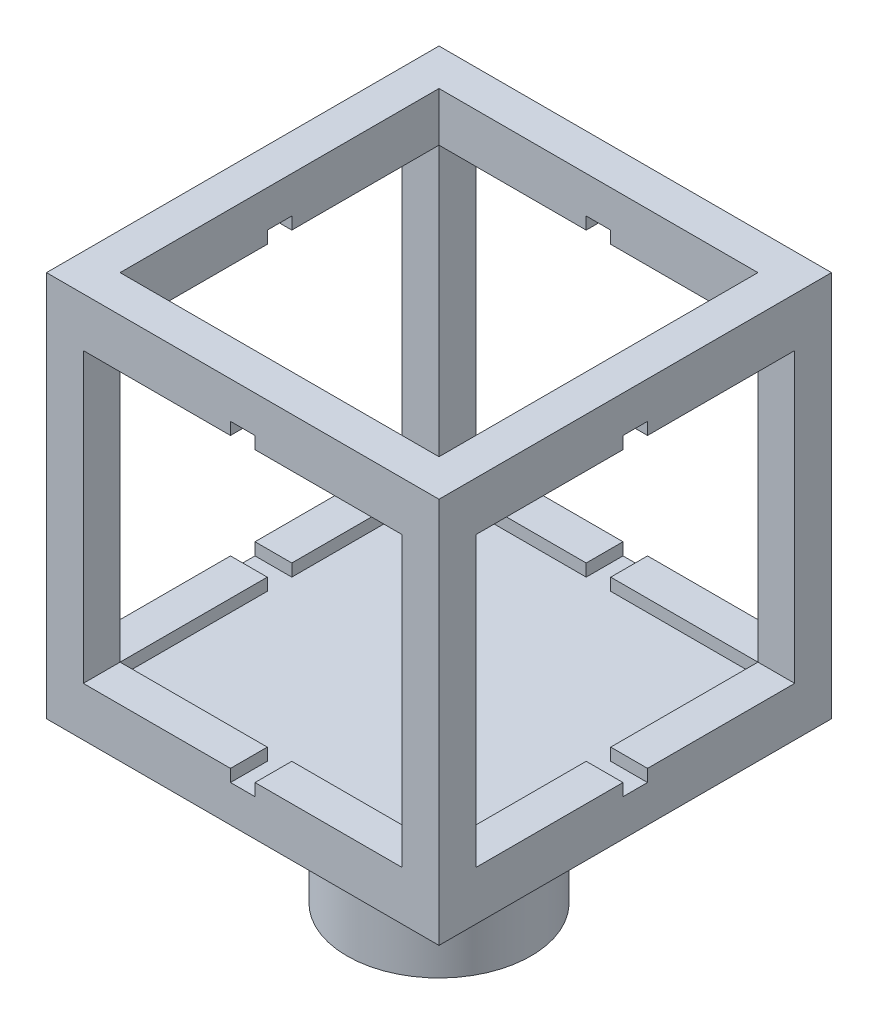
SolidWorks part; units mm, degrees
ref_plane "Plan de face" through (0, 0, 0) normal (0, 0, 1) x (1, 0, 0)
ref_plane "Plan de dessus" through (0, 0, 0) normal (0, 1, 0) x (1, 0, 0)
ref_plane "Plan de droite" through (0, 0, 0) normal (1, 0, 0) x (0, 0, -1)
sketch "Esquisse1" plane through (0, 0, 0) normal (0, 1, 0) x (1, 0, 0)
  circle A0 centre (0, 0) radius 7.5
  dimension "D1" = 15
extrude "Boss.-Extru.1" add sketch "Esquisse1" against normal blind 12
sketch "Esquisse2" plane through (0, 0, 0) normal (0, 1, 0) x (1, 0, 0)
  circle A0 centre (0, 0) radius 8.5
  dimension "D1" = 17
extrude "Boss.-Extru.2" add sketch "Esquisse2" along normal blind 1
sketch "Esquisse3" plane through (0, 1, 0) normal (0, 1, 0) x (1, 0, 0)
  line L1 (-13, -13) -> (13, -13)
  line L2 (-13, -13) -> (-13, 13)
  line L3 (-13, 13) -> (13, 13)
  line L4 (13, -13) -> (13, 13)
  line L5 (-13, -13) -> (13, 13) construction
  line L6 (-13, 13) -> (13, -13) construction
  line L7 (-16, -16) -> (16, -16)
  line L8 (-16, -16) -> (-16, 16)
  line L9 (-16, 16) -> (16, 16)
  line L10 (16, -16) -> (16, 16)
  line L11 (-16, -16) -> (16, 16) construction
  line L12 (-16, 16) -> (16, -16) construction
  point P0 (0, 0)
  point P6 (0, 0)
  circle M7 centre (0, 0) radius 8.5
  dimension "D1" = 26
  dimension "D2" = 26
  dimension "D3" = 3
  dimension "D4" = 3
extrude "Boss.-Extru.3" add sketch "Esquisse3" along normal blind 31.5 separate body contours L1 L4 L3 L2 M7 | M7 | L7 L10 L9 L8 L4 L1 L2 L3
sketch3d "Esquisse3D1" plane through (0, 0, 0) normal (0, 0, 1) x (1, 0, 0)
  dimension "D1" = 3
sketch "Esquisse7" plane through (0, 4, 0) normal (0, -1, 0) x (-1, 0, 0)
  line L1 (-13, 13) -> (13, 13)
  line L2 (-13, 13) -> (-13, -13)
  line L3 (-13, -13) -> (13, -13)
  line L4 (13, 13) -> (13, -13)
extrude "Enlèv. mat.-Extru.2" cut sketch "Esquisse7" against normal through all
sketch "Esquisse8" plane through (-16, 0, 0) normal (-1, 0, 0) x (0, 0, 1)
  line L0 (-16, 32.5) -> (-16, 1) construction
  line L1 (-13, 4) -> (13, 4)
  line L2 (-13, 4) -> (-13, 29.5)
  line L3 (-13, 29.5) -> (13, 29.5)
  line L4 (13, 4) -> (13, 29.5)
  line L5 (16, 32.5) -> (16, 1) construction
  line L6 (16, 1) -> (-16, 1) construction
  line L7 (16, 32.5) -> (-16, 32.5) construction
  dimension "D1" = 3
  dimension "D2" = 3
  dimension "D3" = 3
  dimension "D4" = 3
extrude "Enlèv. mat.-Extru.3" cut sketch "Esquisse8" against normal through all
sketch "Esquisse9" plane through (0, 0, -16) normal (0, 0, -1) x (-1, 0, 0)
  line L0 (16, 1) -> (-16, 1) construction
  line L1 (-13, 4) -> (13, 4)
  line L2 (-13, 4) -> (-13, 29.5)
  line L3 (-13, 29.5) -> (13, 29.5)
  line L4 (13, 4) -> (13, 29.5)
  line L5 (16, 32.5) -> (-16, 32.5) construction
  line L6 (-16, 32.5) -> (-16, 1) construction
  line L7 (16, 32.5) -> (16, 1) construction
  dimension "D1" = 3
  dimension "D2" = 3
  dimension "D3" = 3
  dimension "D4" = 3
extrude "Enlèv. mat.-Extru.4" cut sketch "Esquisse9" against normal through all
sketch "Esquisse10" plane through (0, 4, 0) normal (0, 1, 0) x (1, 0, 0)
  line L0 (-16, 0) -> (16, 0) construction
  line L1 (-16, -16) -> (-16, 16) construction
  line L2 (16, -16) -> (16, 16) construction
  line L3 (0, 16) -> (0, -16) construction
  line L4 (-16, 16) -> (16, 16) construction
  line L5 (-16, -16) -> (16, -16) construction
  line L6 (1, 13) -> (1, 16)
  line L7 (-13, 13) -> (-1, 13)
  line L8 (-13, 13) -> (-13, 16)
  line L9 (-13, 16) -> (-1, 16)
  line L10 (-1, 13) -> (-1, 16)
  line L11 (13, 16) -> (1, 16)
  line L12 (13, 13) -> (13, 16)
  line L13 (13, 13) -> (1, 13)
  line L14 (13, 13) -> (13, 1)
  line L15 (13, 13) -> (16, 13)
  line L16 (16, 13) -> (16, 1)
  line L17 (13, 1) -> (16, 1)
  line L18 (13, -1) -> (16, -1)
  line L19 (16, -13) -> (16, -1)
  line L20 (13, -13) -> (16, -13)
  line L21 (13, -13) -> (13, -1)
  line L22 (13, -13) -> (1, -13)
  line L23 (13, -13) -> (13, -16)
  line L24 (13, -16) -> (1, -16)
  line L25 (1, -13) -> (1, -16)
  line L26 (-1, -13) -> (-1, -16)
  line L27 (-13, -16) -> (-1, -16)
  line L28 (-13, -13) -> (-13, -16)
  line L29 (-13, -13) -> (-1, -13)
  line L30 (-13, -13) -> (-13, -1)
  line L31 (-13, -13) -> (-16, -13)
  line L32 (-16, -13) -> (-16, -1)
  line L33 (-13, -1) -> (-16, -1)
  line L34 (-13, 1) -> (-16, 1)
  line L35 (-16, 13) -> (-16, 1)
  line L36 (-13, 13) -> (-16, 13)
  line L37 (-13, 13) -> (-13, 1)
  point P21 (0, 0)
  point P22 (0, 0)
  point P23 (16, 13)
  line M10 (-16, -13) -> (-13, -13)
  line M11 (-13, -13) -> (-13, -16)
  line M12 (-13, -16) -> (13, -16)
  line M13 (13, -16) -> (13, -13)
  line M14 (13, -13) -> (16, -13)
  line M15 (16, -13) -> (16, 13)
  line M16 (16, 13) -> (13, 13)
  line M17 (13, 13) -> (13, 16)
  line M18 (13, 16) -> (-13, 16)
  line M19 (-13, 16) -> (-13, 13)
  line M20 (-13, 13) -> (-16, 13)
  line M21 (-16, 13) -> (-16, -13)
  dimension "D1" = 1
  dimension "D2" = 4
extrude "Boss.-Extru.5" add sketch "Esquisse10" along normal blind 1 contours L7 L10 M18 M19 | L13 L6 M17 M18 | L14 L17 M15 M16 | L21 L18 M14 M15 | L22 L25 M12 M13 | L29 L26 M11 M12 | L30 L33 M21 M10 | L37 L34 M20 M21
sketch "Esquisse12" plane through (0, 29.5, 0) normal (0, -1, 0) x (1, 0, 0)
  line L0 (-13, 13) -> (-13, -13) construction
  line L1 (-16, 13) -> (-13, 13)
  line L2 (-16, 13) -> (-16, 1)
  line L3 (-16, 1) -> (-13, 1)
  line L4 (-13, 13) -> (-13, 1)
  line L5 (-16, 16) -> (-16, -16) construction
  line L6 (-13, -13) -> (-16, -13)
  line L7 (-13, -13) -> (-13, -1)
  line L8 (-13, -1) -> (-16, -1)
  line L9 (-16, -13) -> (-16, -1)
  line L10 (16, 16) -> (16, -16) construction
  line L11 (13, 13) -> (16, 13)
  line L12 (13, 13) -> (13, 1)
  line L13 (13, 1) -> (16, 1)
  line L14 (16, 13) -> (16, 1)
  line L16 (13, -13) -> (16, -13)
  line L17 (13, -13) -> (13, -1)
  line L18 (13, -1) -> (16, -1)
  line L19 (16, -13) -> (16, -1)
  dimension "D1" = 2
  dimension "D2" = 1
  dimension "D3" = 2
  dimension "D4" = 1
extrude "Boss.-Extru.9" add sketch "Esquisse12" along normal blind 1
sketch "Esquisse13" plane through (0, 29.5, 0) normal (0, -1, 0) x (1, 0, 0)
  line L0 (-16, -16) -> (16, -16) construction
  line L1 (-13, -13) -> (-1, -13)
  line L2 (-13, -13) -> (-13, -16)
  line L3 (-13, -16) -> (-1, -16)
  line L4 (-1, -13) -> (-1, -16)
  line L5 (-16, 16) -> (16, 16) construction
  line L6 (13, -13) -> (1, -13)
  line L7 (13, -13) -> (13, -16)
  line L8 (13, -16) -> (1, -16)
  line L9 (1, -13) -> (1, -16)
  line L10 (-13, 13) -> (-1, 13)
  line L11 (-13, 13) -> (-13, 16)
  line L12 (-13, 16) -> (-1, 16)
  line L13 (-1, 13) -> (-1, 16)
  line L15 (13, 13) -> (1, 13)
  line L16 (13, 13) -> (13, 16)
  line L17 (13, 16) -> (1, 16)
  line L18 (1, 13) -> (1, 16)
  point P12 (-1, -14.5)
  dimension "D1" = 1
  dimension "D2" = 1
  dimension "D3" = 1
  dimension "D4" = 1
extrude "Boss.-Extru.10" add sketch "Esquisse13" along normal blind 1
